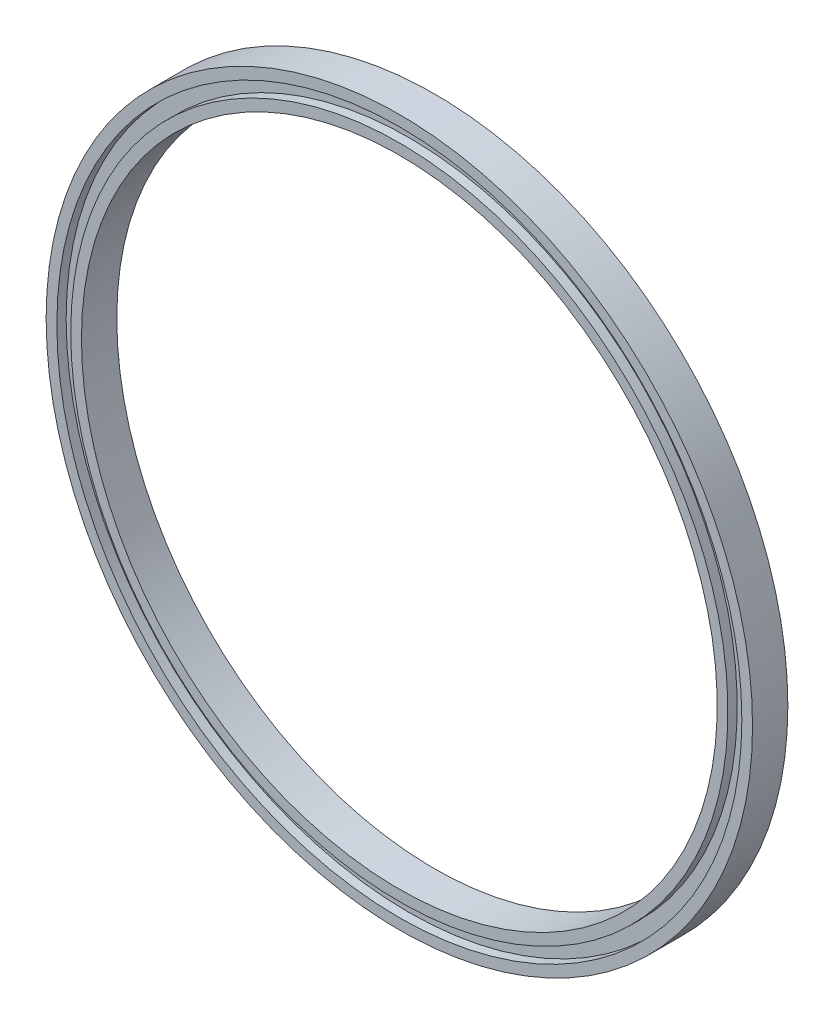
SolidWorks part; units mm, degrees
material "GCr15"
ref_plane "前视基准面" through (0, 0, 0) normal (0, 0, 1) x (1, 0, 0)
ref_plane "上视基准面" through (0, 0, 0) normal (0, 1, 0) x (1, 0, 0)
ref_plane "右视基准面" through (0, 0, 0) normal (1, 0, 0) x (0, 0, -1)
sketch "草图1" plane through (0, 0, 0) normal (1, 0, 0) x (0, 0, -1)
  line L0 (0, 73.165) -> (0, 0) construction
  line L1 (0, 0) -> (-19.4628, 0) construction
  line L2 (7.6197, 60.325) -> (-15.6509, 60.325) construction
  line L3 (-3.175, 63.5) -> (3.175, 63.5)
  line L4 (3.175, 63.5) -> (3.175, 61.575)
  line L5 (3.175, 61.575) -> (1.5, 61.575)
  line L6 (1.5, 61.575) -> (1.5, 59.075)
  line L7 (3.175, 59.075) -> (1.5, 59.075)
  line L8 (3.175, 57.15) -> (3.175, 59.075)
  line L9 (-3.175, 57.15) -> (3.175, 57.15)
  line L10 (-3.175, 57.15) -> (-3.175, 59.075)
  line L11 (-3.175, 59.075) -> (-1.5, 59.075)
  line L12 (-1.5, 61.575) -> (-1.5, 59.075)
  line L13 (-3.175, 61.575) -> (-1.5, 61.575)
  line L14 (-3.175, 63.5) -> (-3.175, 61.575)
  point P12 (1.5, 60.325)
  point P15 (-1.5, 60.325)
  point P17 (0, 57.15)
  point P22 (0, 63.5)
  dimension "D1" = 114.3
  dimension "D2" = 127
  dimension "D3" = 6.35
  dimension "D4" = 2.5
  dimension "D5" = 3
revolve "旋转1" add sketch "草图1" angle 360 about L1
